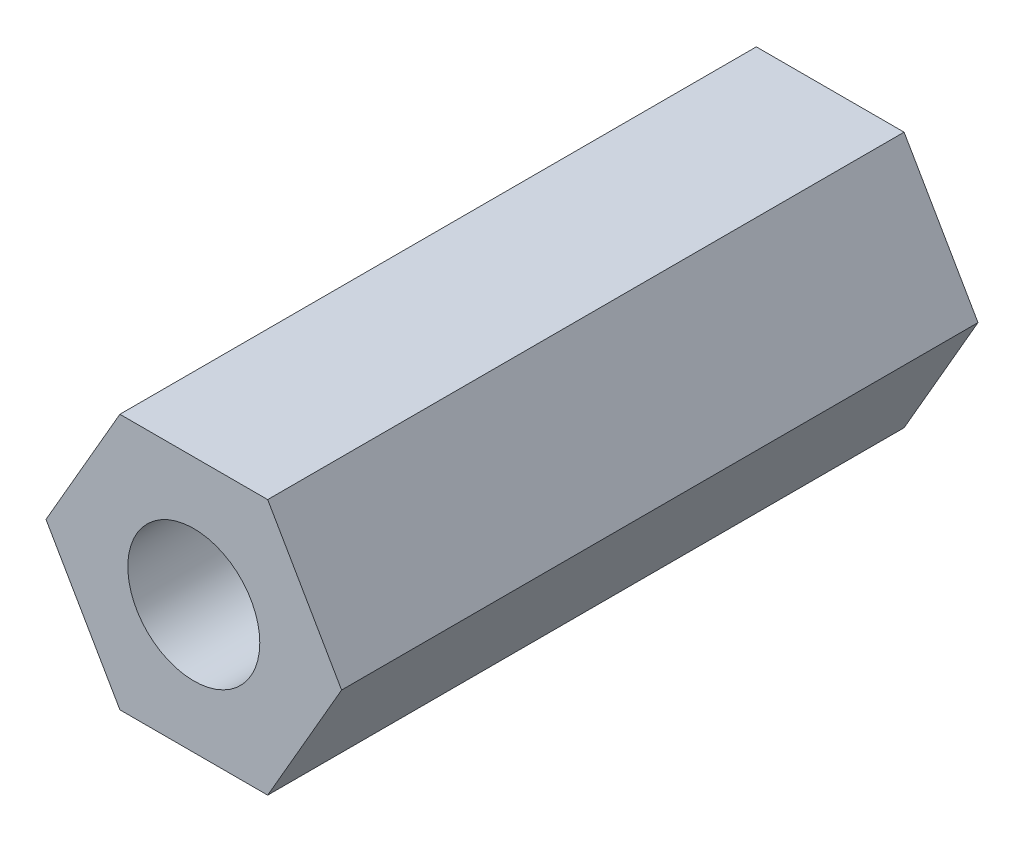
SolidWorks part; units mm, degrees
ref_plane "Ön Düzlem" through (0, 0, 0) normal (0, 0, 1) x (1, 0, 0)
ref_plane "Üst Düzlem" through (0, 0, 0) normal (0, 1, 0) x (1, 0, 0)
ref_plane "Sağ Düzlem" through (0, 0, 0) normal (1, 0, 0) x (0, 0, -1)
sketch "Çizim1" plane through (0, 0, 0) normal (0, 0, 1) x (1, 0, 0)
  line L1 (1.5675, -2.715) -> (3.135, 0)
  line L2 (3.135, 0) -> (1.5675, 2.715)
  line L3 (1.5675, 2.715) -> (-1.5675, 2.715)
  line L4 (-1.5675, 2.715) -> (-3.135, 0)
  line L5 (-3.135, 0) -> (-1.5675, -2.715)
  line L6 (-1.5675, -2.715) -> (1.5675, -2.715)
  circle A0 centre (0, 0) radius 2.715 construction
  circle A1 centre (0, 0) radius 1.4
  dimension "D2" = 2.8
  dimension "D1" = 5.43
extrude "Yükseklik-Ekstrüzyon1" add sketch "Çizim1" along normal blind 13.5
